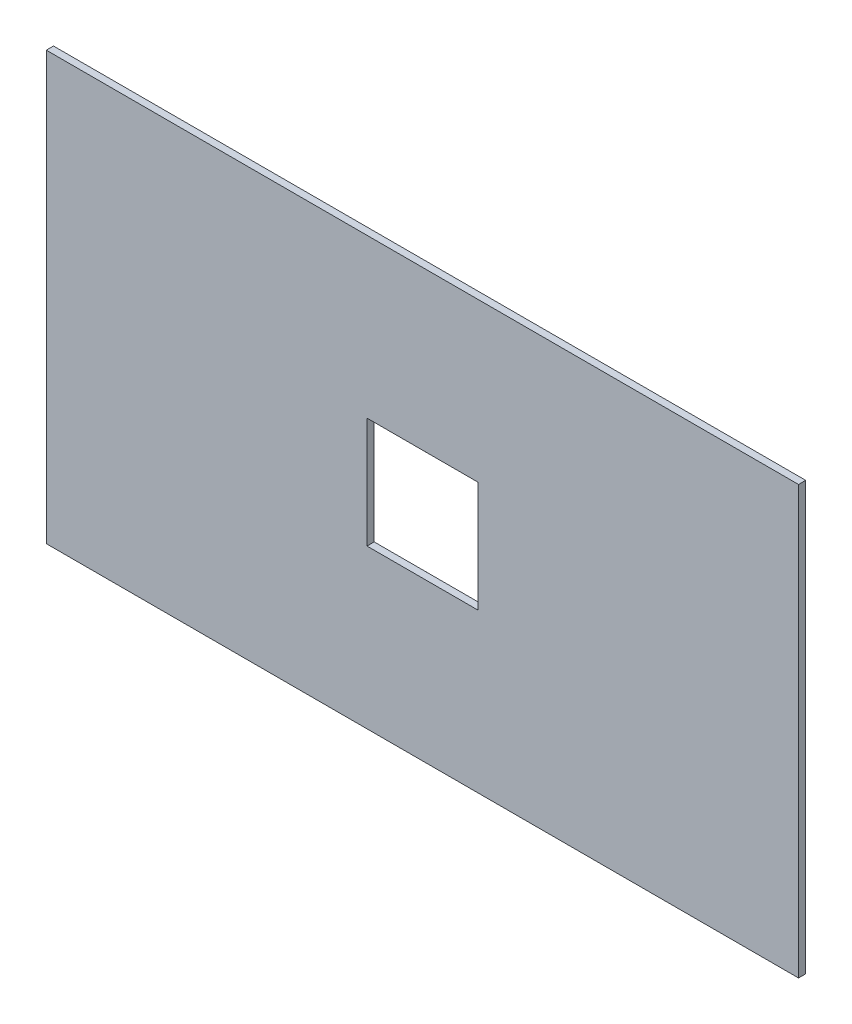
SolidWorks part; units mm, degrees
ref_plane "Front Plane" through (0, 0, 0) normal (0, 0, 1) x (1, 0, 0)
ref_plane "Top Plane" through (0, 0, 0) normal (0, 1, 0) x (1, 0, 0)
ref_plane "Right Plane" through (0, 0, 0) normal (1, 0, 0) x (0, 0, -1)
sketch "Sketch1" plane through (0, 0, 0) normal (0, 0, 1) x (1, 0, 0)
  line L1 (-139.7, -79.375) -> (139.7, -79.375)
  line L2 (-139.7, -79.375) -> (-139.7, 79.375)
  line L3 (-139.7, 79.375) -> (139.7, 79.375)
  line L4 (139.7, -79.375) -> (139.7, 79.375)
  line L5 (-139.7, -79.375) -> (139.7, 79.375) construction
  line L6 (-139.7, 79.375) -> (139.7, -79.375) construction
  point P0 (0, 0)
extrude "Boss-Extrude1" add sketch "Sketch1" along normal blind 2.667
sketch "Sketch2" plane through (0, 0, 0) normal (0, 0, 1) x (1, 0, 0)
  line L1 (-20.574, -20.574) -> (20.574, -20.574)
  line L2 (-20.574, -20.574) -> (-20.574, 20.574)
  line L3 (-20.574, 20.574) -> (20.574, 20.574)
  line L4 (20.574, -20.574) -> (20.574, 20.574)
  line L5 (-20.574, -20.574) -> (20.574, 20.574) construction
  line L6 (-20.574, 20.574) -> (20.574, -20.574) construction
  point P0 (0, 0)
extrude "Cut-Extrude1" cut sketch "Sketch2" along normal blind 47.752
